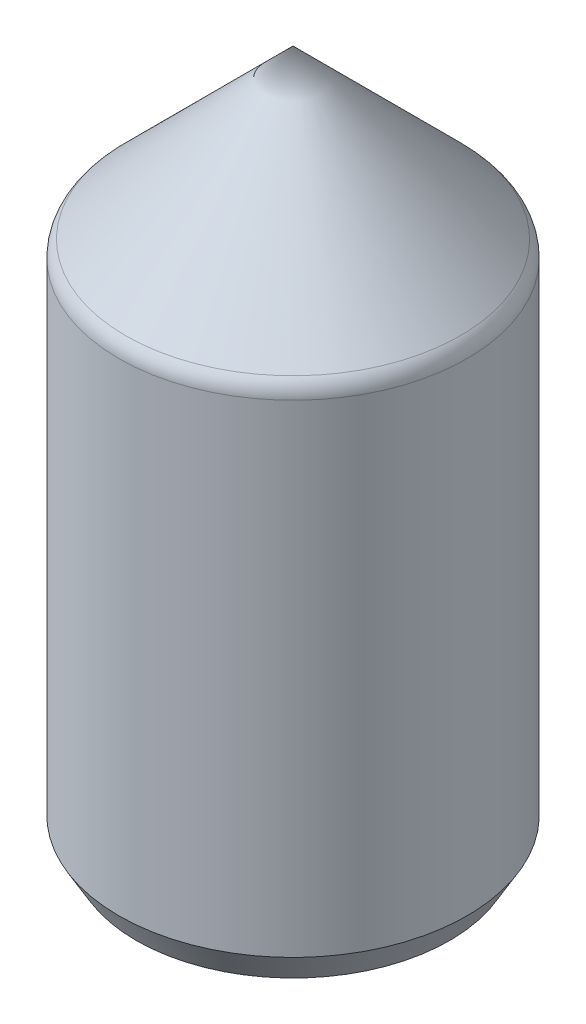
SolidWorks part; units mm, degrees
material "AISI 1045 Steel, cold drawn"
ref_plane "Front Plane" through (0, 0, 0) normal (0, 0, 1) x (1, 0, 0)
ref_plane "Top Plane" through (0, 0, 0) normal (0, 1, 0) x (1, 0, 0)
ref_plane "Right Plane" through (0, 0, 0) normal (1, 0, 0) x (0, 0, -1)
sketch "Sketch1" plane through (0, 0, 0) normal (0, 0, 1) x (1, 0, 0)
  line L0 (1.5, 4.5) -> (0, 6)
  line L1 (0, 0) -> (1.5, 0)
  line L2 (0, 0) -> (0, 3.4783)
  line L4 (1.5, 0) -> (1.5, 4.5)
  line L5 (0, 6) -> (0, 3.4783)
  dimension "D1" = 45
  dimension "D2" = 6
  dimension "D3" = 1.5
revolve "Revolve1" add sketch "Sketch1" angle 360 about L5
fillet "Fillet1" radius 0.2 1 edges at (0, 4.5, 1.5)
sketch "Sketch2" plane through (0, 0, 0) normal (0, -1, 0) x (1, 0, 0)
  line L1 (0, 0.866) -> (-0.75, 0.433)
  line L2 (-0.75, 0.433) -> (-0.75, -0.433)
  line L3 (-0.75, -0.433) -> (0, -0.866)
  line L4 (0, -0.866) -> (0.75, -0.433)
  line L5 (0.75, -0.433) -> (0.75, 0.433)
  line L6 (0.75, 0.433) -> (0, 0.866)
  circle A0 centre (0, 0) radius 0.75 construction
  dimension "D1" = 1.5
extrude "Cut-Extrude1" cut sketch "Sketch2" against normal blind 2.1 and the other way through all
chamfer "Chamfer1" distance 0.15 angle 60 1 edges at (0, 0, 1.5)
